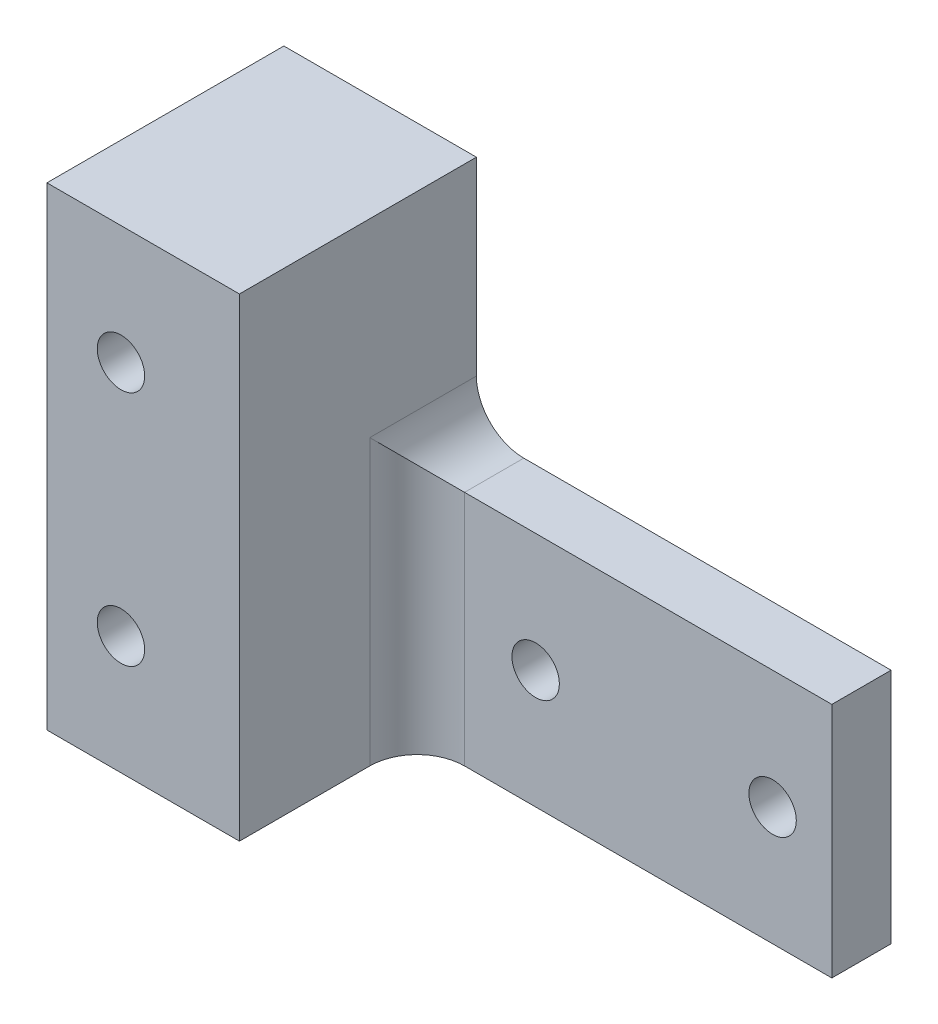
SolidWorks part; units mm, degrees
ref_plane "Front Plane" through (0, 0, 0) normal (0, 0, 1) x (1, 0, 0)
ref_plane "Top Plane" through (0, 0, 0) normal (0, 1, 0) x (1, 0, 0)
ref_plane "Right Plane" through (0, 0, 0) normal (1, 0, 0) x (0, 0, -1)
sketch "Sketch1" plane through (0, 0, 0) normal (0, 0, 1) x (1, 0, 0)
  line L0 (0, 0) -> (0, 50.8)
  line L1 (0, 50.8) -> (25.4, 50.8)
  line L2 (25.4, 50.8) -> (25.4, 25.4)
  line L3 (25.4, 25.4) -> (69.85, 25.4)
  line L4 (69.85, 25.4) -> (69.85, 0)
  line L5 (69.85, 0) -> (0, 0)
  dimension "D1" = 50.8
  dimension "D2" = 25.4
  dimension "3" = 69.85
extrude "Boss-Extrude1" add sketch "Sketch1" along normal blind 25.4
sketch "Sketch2" plane through (0, 0, 25.4) normal (0, 0, 1) x (1, 0, 0)
  line L0 (25.4, 50.8) -> (0, 50.8) construction
  line L1 (25.4, 25.4) -> (25.4, 50.8) construction
  line L2 (0, 0) -> (69.85, 0) construction
  circle A0 centre (12.7, 38.1) radius 2.54
  circle A1 centre (12.7, 12.7) radius 2.54
  circle A2 centre (38.1, 12.7) radius 2.54
  circle A3 centre (63.5, 12.7) radius 2.54
  dimension "D1" = 5.08
  dimension "D2" = 12.7
  dimension "D3" = 12.7
  dimension "D4" = 12.7
  dimension "D5" = 3
extrude "Cut-Extrude1" cut sketch "Sketch2" against normal through all
sketch "Sketch3" plane through (0, 0, 25.4) normal (0, 0, 1) x (1, 0, 0)
  line L0 (25.4, 50.8) -> (0, 50.8) construction
  line L1 (0, 0) -> (4.7625, 0)
  line L2 (0, 0) -> (0, 50.8)
  line L3 (0, 50.8) -> (4.7625, 50.8)
  line L4 (4.7625, 0) -> (4.7625, 50.8)
  dimension "D1" = 4.7625
extrude "Cut-Extrude2" cut sketch "Sketch3" against normal through all
sketch "Sketch4" plane through (0, 0, 0) normal (0, -1, 0) x (1, 0, 0)
  line L5 (69.85, 25.4) -> (25.4, 25.4)
  line L6 (69.85, 25.4) -> (69.85, 6.35)
  line L7 (69.85, 6.35) -> (25.4, 6.35)
  line L8 (25.4, 25.4) -> (25.4, 6.35)
  dimension "D1" = 19.05
  dimension "D2" = 44.45
extrude "Cut-Extrude3" cut sketch "Sketch4" against normal through all
fillet "Fillet1" radius 5.08 2 edges at (25.4, 25.4, 3.175) (25.4, 12.7, 6.35)
sketch "Sketch6" plane through (0, 0, 0) normal (0, 0, -1) x (-1, 0, 0)
  circle A0 centre (-12.7, 38.1) radius 4.064
  dimension "D1" = 8.128
extrude "Cut-Extrude5" cut sketch "Sketch6" against normal blind 7.62
